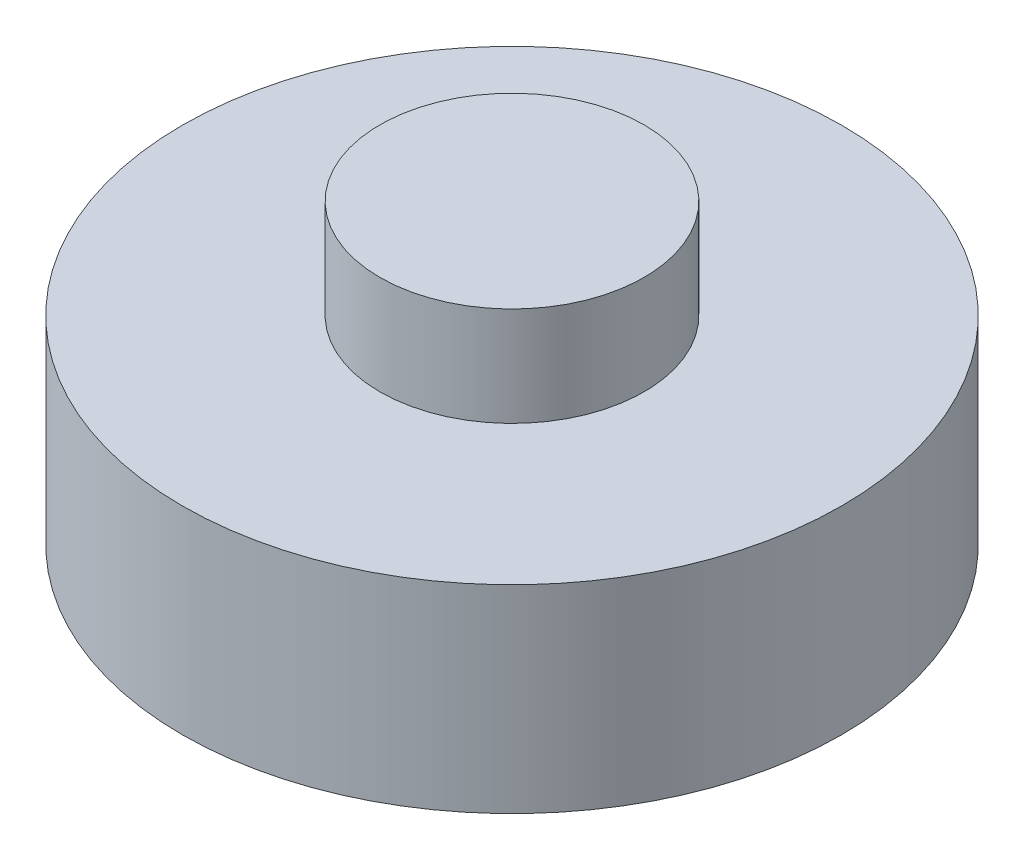
SolidWorks part; units mm, degrees
ref_plane "Front Plane" through (0, 0, 0) normal (0, 0, 1) x (1, 0, 0)
ref_plane "Top Plane" through (0, 0, 0) normal (0, 1, 0) x (1, 0, 0)
ref_plane "Right Plane" through (0, 0, 0) normal (1, 0, 0) x (0, 0, -1)
sketch "Sketch1" plane through (0, 0, 0) normal (0, 1, 0) x (1, 0, 0)
  circle A0 centre (0, 0) radius 49.9
  dimension "D1" = 99.8
extrude "Boss-Extrude1" add sketch "Sketch1" along normal blind 30
sketch "Sketch2" plane through (0, 30, 0) normal (0, 1, 0) x (1, 0, 0)
  circle A0 centre (0, 0) radius 20
  dimension "D1" = 40
extrude "Boss-Extrude2" add sketch "Sketch2" along normal blind 15
